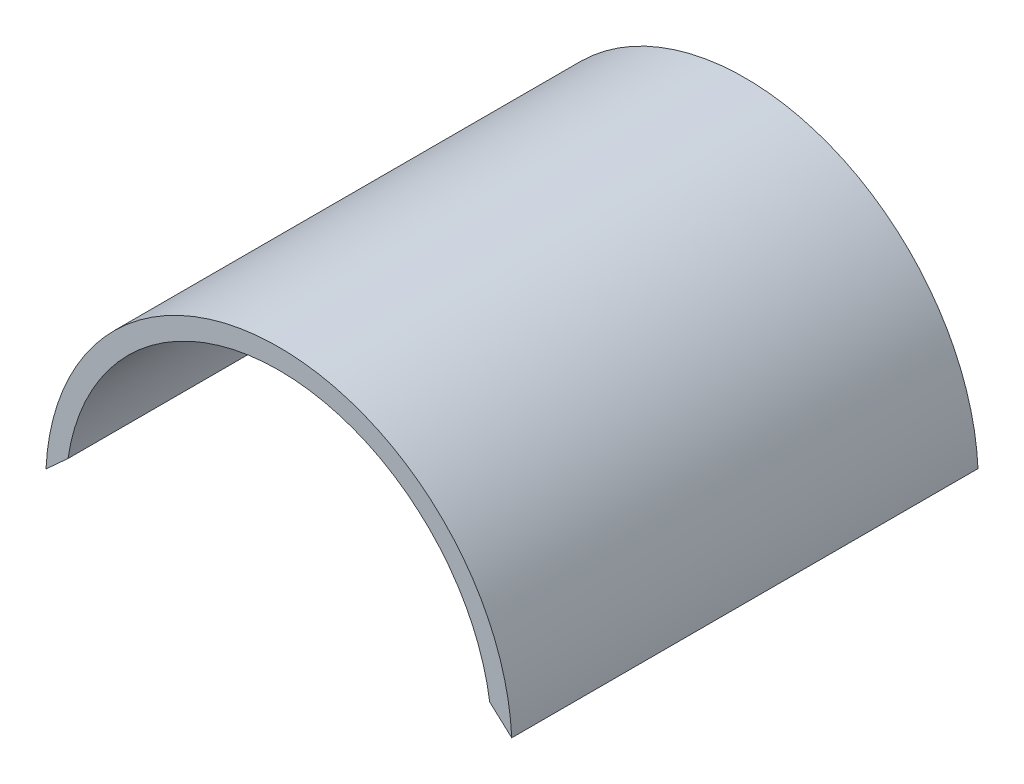
SolidWorks part; units mm, degrees
ref_plane "Front Plane" through (0, 0, 0) normal (0, 0, 1) x (1, 0, 0)
ref_plane "Top Plane" through (0, 0, 0) normal (0, 1, 0) x (1, 0, 0)
ref_plane "Right Plane" through (0, 0, 0) normal (1, 0, 0) x (0, 0, -1)
sketch "Sketch1" plane through (0, 0, 0) normal (0, 0, 1) x (1, 0, 0)
  line L0 (0, 0) -> (0, 44.45) construction
  line L1 (-40.2039, 5.9378) -> (40.2039, 5.9378) construction
  line L2 (-44.399, 2.1278) -> (44.399, 2.1278) construction
  line L3 (-40.2039, 5.9378) -> (-44.399, 2.1278)
  line L4 (40.2039, 5.9378) -> (44.399, 2.1278)
  arc A0 (44.399, 2.1278) -> (-44.399, 2.1278) centre (0, 0) ccw
  arc A1 (40.2039, 5.9378) -> (-40.2039, 5.9378) centre (0, 0) ccw
  dimension "D1" = 88.9
  dimension "D2" = 3.81
  dimension "D3" = 3.81
extrude "Boss-Extrude1" add sketch "Sketch1" along normal blind 88.9
